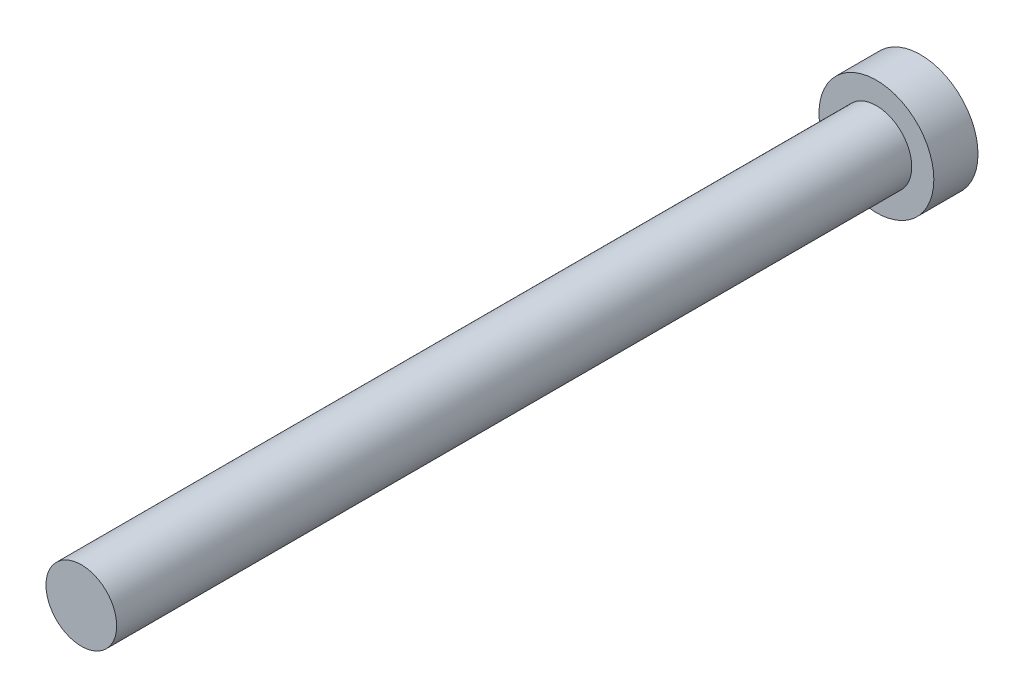
SolidWorks part; units mm, degrees
ref_plane "前视基准面" through (0, 0, 0) normal (0, 0, 1) x (1, 0, 0)
ref_plane "上视基准面" through (0, 0, 0) normal (0, 1, 0) x (1, 0, 0)
ref_plane "右视基准面" through (0, 0, 0) normal (1, 0, 0) x (0, 0, -1)
sketch "草图1" plane through (0, 0, 0) normal (0, 0, 1) x (1, 0, 0)
  circle A0 centre (0, 0) radius 6.5
  dimension "D1" = 13
extrude "凸台-拉伸1" add sketch "草图1" along normal blind 5
sketch "草图2" plane through (0, 0, 5) normal (0, 0, 1) x (1, 0, 0)
  circle A0 centre (0, 0) radius 4
  dimension "D1" = 8
extrude "凸台-拉伸2" add sketch "草图2" along normal blind 90
